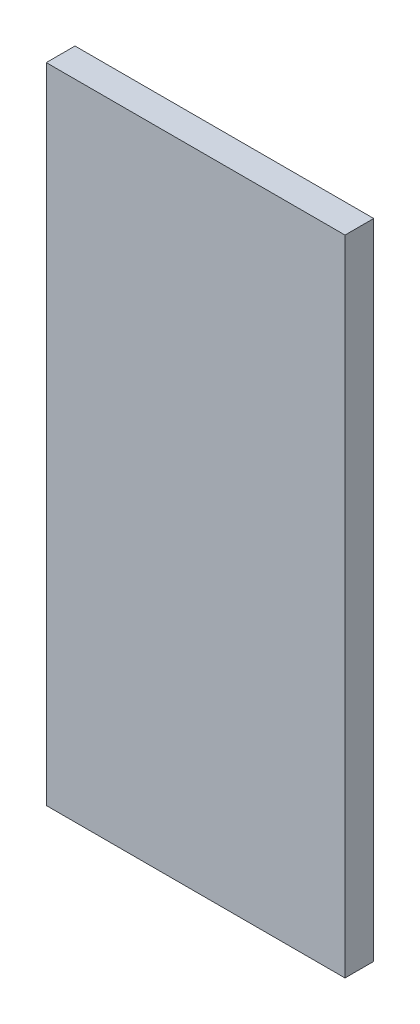
SolidWorks part; units mm, degrees
ref_plane "Front Plane" through (0, 0, 0) normal (0, 0, 1) x (1, 0, 0)
ref_plane "Top Plane" through (0, 0, 0) normal (0, 1, 0) x (1, 0, 0)
ref_plane "Right Plane" through (0, 0, 0) normal (1, 0, 0) x (0, 0, -1)
sketch "Sketch1" plane through (0, 0, 0) normal (0, 0, 1) x (1, 0, 0)
  line L1 (-33.02, 71.12) -> (33.02, 71.12)
  line L2 (-33.02, 71.12) -> (-33.02, -71.12)
  line L3 (-33.02, -71.12) -> (33.02, -71.12)
  line L4 (33.02, 71.12) -> (33.02, -71.12)
  point P4 (0, 71.12)
  point P6 (-33.02, 0)
  dimension "D1" = 66.04
  dimension "D2" = 142.24
extrude "Boss-Extrude1" add sketch "Sketch1" along normal blind 6.35
